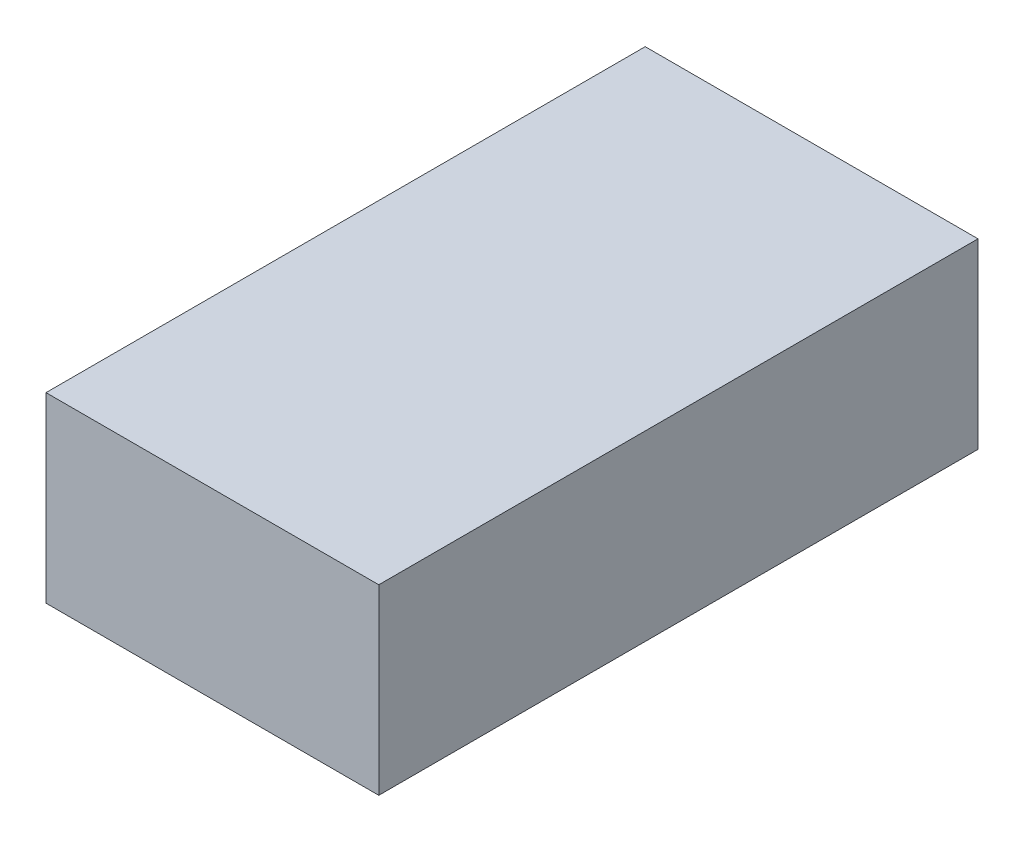
SolidWorks part; units mm, degrees
ref_plane "Front Plane" through (0, 0, 0) normal (0, 0, 1) x (1, 0, 0)
ref_plane "Top Plane" through (0, 0, 0) normal (0, 1, 0) x (1, 0, 0)
ref_plane "Right Plane" through (0, 0, 0) normal (1, 0, 0) x (0, 0, -1)
sketch "CurveSketch" plane through (0, 0, 0) normal (0, 0, 1) x (1, 0, 0)
  line L0 (-20.0525, -1.8635) -> (11.6665, -1.8635)
  line L1 (11.6665, -1.8635) -> (11.6665, 15.5175)
  line L2 (11.6665, 15.5175) -> (-20.0525, 15.5175)
  line L3 (-20.0525, 15.5175) -> (-20.0525, -1.8635)
extrude "CurveBoss" add sketch "CurveSketch" along normal blind 57.113
